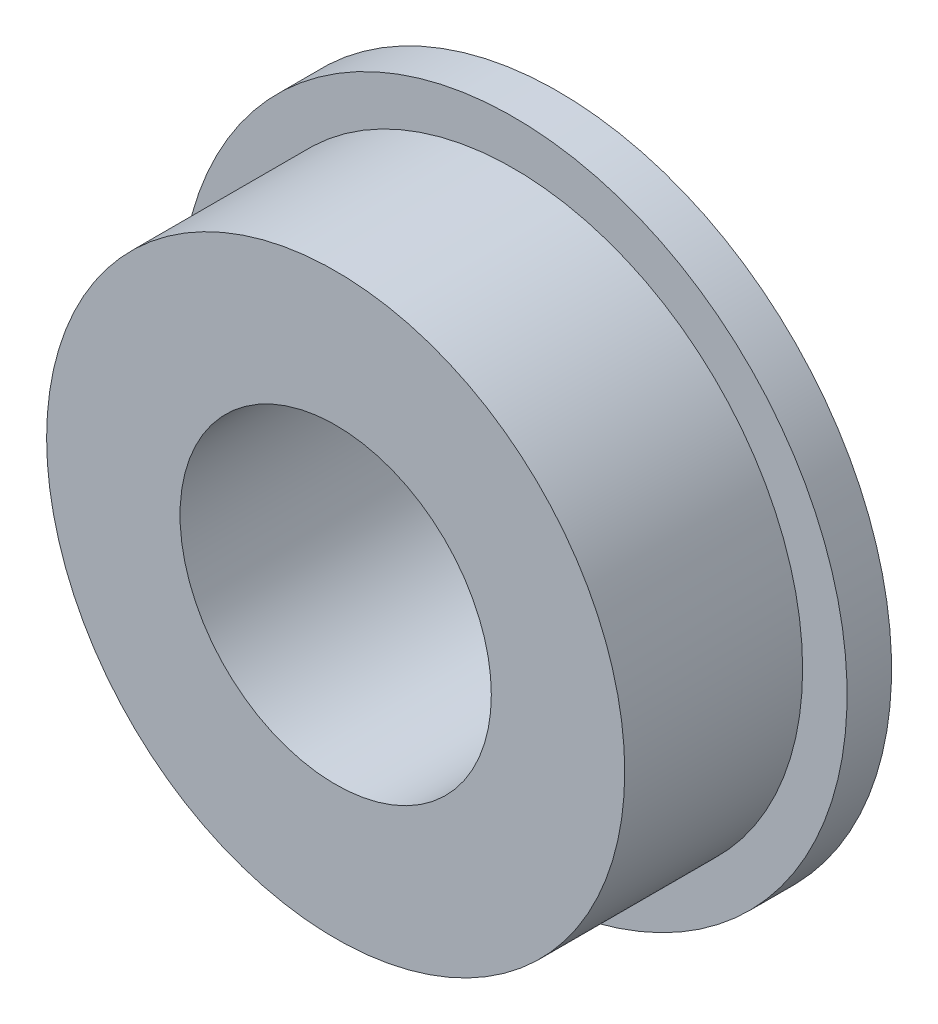
SolidWorks part; units mm, degrees
ref_plane "正面" through (0, 0, 0) normal (0, 0, 1) x (1, 0, 0)
ref_plane "平面" through (0, 0, 0) normal (0, 1, 0) x (1, 0, 0)
ref_plane "右側面" through (0, 0, 0) normal (1, 0, 0) x (0, 0, -1)
sketch "ｽｹｯﾁ1" plane through (0, 0, 0) normal (0, 0, 1) x (1, 0, 0)
  circle A0 centre (0, 0) radius 6.5
  dimension "D1" = 13
extrude "ﾎﾞｽ - 押し出し1" add sketch "ｽｹｯﾁ1" along normal blind 5
sketch "ｽｹｯﾁ2" plane through (0, 0, 0) normal (0, 0, -1) x (-1, 0, 0)
  circle A0 centre (0, 0) radius 7.5
  circle A1 centre (0, 0) radius 6.5 construction
  dimension "D1" = 1
extrude "ﾎﾞｽ - 押し出し2" add sketch "ｽｹｯﾁ2" against normal blind 1
sketch "ｽｹｯﾁ3" plane through (0, 0, 5) normal (0, 0, 1) x (1, 0, 0)
  circle A0 centre (0, 0) radius 3.5
  dimension "D1" = 7
extrude "ｶｯﾄ - 押し出し1" cut sketch "ｽｹｯﾁ3" against normal through all
